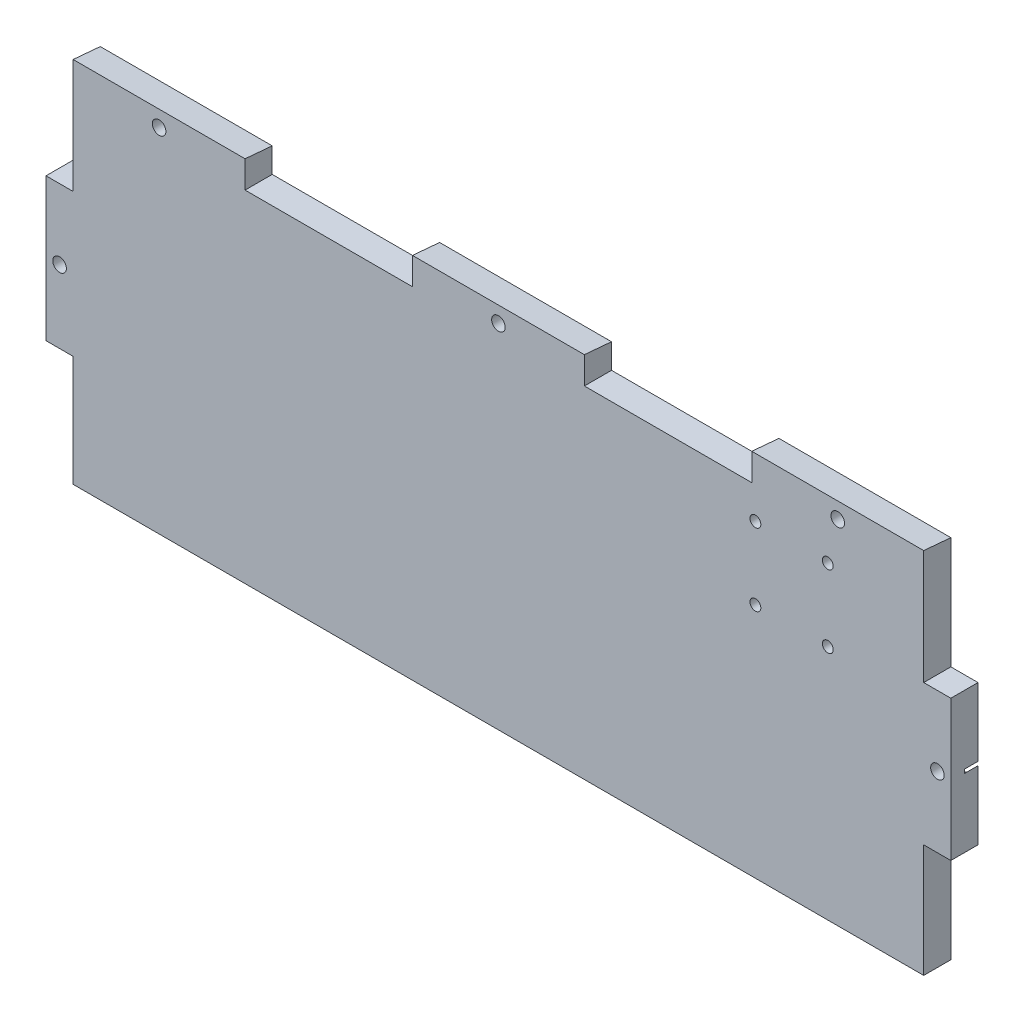
SolidWorks part; units mm, degrees
ref_plane "Plan de face" through (0, 0, 0) normal (0, 0, 1) x (1, 0, 0)
ref_plane "Plan de dessus" through (0, 0, 0) normal (0, 1, 0) x (1, 0, 0)
ref_plane "Plan de droite" through (0, 0, 0) normal (1, 0, 0) x (0, 0, -1)
sketch "Esquisse1" plane through (0, 0, 0) normal (0, 0, 1) x (1, 0, 0)
  line L1 (0, 0) -> (-188, 0)
  line L2 (0, 0) -> (0, 81.33)
  line L3 (0, 81.33) -> (-188, 81.33)
  line L4 (-188, 0) -> (-188, 81.33)
  dimension "D1" = 188
  dimension "D2" = 81.33
extrude "Boss.-Extru.1" add sketch "Esquisse1" along normal blind 6
sketch "Esquisse2" plane through (-188, 0, 0) normal (-1, 0, 0) x (0, 0, 1)
  line L0 (6, 81.33) -> (0, 80.8051)
  line L1 (0, 81.33) -> (0, 0) construction
  line L2 (6, 81.33) -> (6, 0) construction
  dimension "D1" = 85
extrude "Enlèv. mat.-Extru.2" cut sketch "Esquisse2" against normal through all and the other way through all flip side to cut contours L0
sketch "Esquisse4" plane through (-188, 0, 0) normal (-1, 0, 0) x (0, 0, 1)
  line L0 (6, 81.33) -> (6, 0) construction
  line L1 (6, 56.0675) -> (0, 56.0675)
  line L2 (6, 56.0675) -> (6, 24.5)
  line L3 (6, 24.5) -> (0, 24.5)
  line L4 (0, 56.0675) -> (0, 24.5)
  line L5 (0, 80.8051) -> (0, 0) construction
  line L6 (6, 81.33) -> (0, 80.8051) construction
  line L7 (6, 0) -> (0, 0) construction
  point P8 (3, 81.0675)
  point P11 (3, 0)
  dimension "D1" = 25
  dimension "D2" = 24.5
extrude "Boss.-Extru.2" add sketch "Esquisse4" along normal blind 6
sketch "Esquisse5" plane through (0, 0, 0) normal (1, 0, 0) x (0, 0, -1)
  line L0 (-6, 0) -> (-6, 81.33) construction
  line L1 (-6, 25) -> (0, 25)
  line L2 (-6, 25) -> (-6, 56.0675)
  line L3 (-6, 56.0675) -> (0, 56.0675)
  line L4 (0, 25) -> (0, 56.0675)
  line L5 (0, 0) -> (0, 80.8051) construction
  line L6 (-6, 0) -> (0, 0) construction
  line L7 (0, 80.8051) -> (-6, 81.33) construction
  point P10 (-3, 81.0675)
  dimension "D1" = 25
  dimension "D2" = 25
extrude "Boss.-Extru.3" add sketch "Esquisse5" along normal blind 6
sketch "Esquisse6" plane through (0, 0, 6) normal (0, 0, 1) x (1, 0, 0)
  line L0 (0, 81.33) -> (-188, 81.33) construction
  line L1 (-150, 81.33) -> (-113, 81.33)
  line L2 (-150, 81.33) -> (-150, 75.33)
  line L3 (-150, 75.33) -> (-113, 75.33)
  line L4 (-113, 81.33) -> (-113, 75.33)
  line L6 (-75, 81.33) -> (-38, 81.33)
  line L7 (-75, 81.33) -> (-75, 75.33)
  line L8 (-75, 75.33) -> (-38, 75.33)
  line L9 (-38, 81.33) -> (-38, 75.33)
  line L11 (0, 56.0675) -> (0, 81.33) construction
  dimension "D1" = 6
  dimension "D2" = 37
  dimension "D3" = 38
  dimension "D4" = 37
  dimension "D5" = 38
extrude "Enlèv. mat.-Extru.3" cut sketch "Esquisse6" against normal blind 6
sketch "Esquisse7" plane through (0, 0, 0) normal (0, 0, -1) x (-1, 0, 0)
  line L0 (113, 80.8051) -> (75, 80.8051) construction
  line L1 (113, 75.33) -> (113, 80.8051) construction
  line L2 (0, 56.0675) -> (0, 80.8051) construction
  line L3 (188, 80.8051) -> (188, 56.0675) construction
  line L4 (194, 56.0675) -> (194, 24.5) construction
  line L5 (194, 56.0675) -> (188, 56.0675) construction
  line L6 (-6, 56.0675) -> (0, 56.0675) construction
  circle A0 centre (94, 77.8051) radius 2.995
  circle A1 centre (19, 77.8051) radius 2.995
  circle A2 centre (169, 77.8051) radius 2.995
  circle A3 centre (191, 40.5675) radius 2.995
  circle A4 centre (-3.034, 40.5675) radius 2.995
  point P10 (113, 78.0675)
  point P23 (-3, 56.0675)
  dimension "D1" = 5.99
  dimension "D3" = 5.99
  dimension "D4" = 5.99
  dimension "D8" = 5.99
  dimension "D11" = 5.99
  dimension "D2" = 3
  dimension "D5" = 19
  dimension "D6" = 19
  dimension "D7" = 19
  dimension "D9" = 3
  dimension "D10" = 15.5
  dimension "D12" = 15.5
extrude "Enlèv. mat.-Extru.4" cut sketch "Esquisse7" against normal blind 3
sketch "Esquisse8" plane through (0, 0, 0) normal (0, 0, -1) x (-1, 0, 0)
  circle A0 centre (-3.034, 40.5675) radius 1.5
  circle A1 centre (19, 77.8051) radius 1.5
  circle A2 centre (94, 77.8051) radius 1.5
  circle A3 centre (169, 77.8051) radius 1.5
  circle A4 centre (191, 40.5675) radius 1.5
extrude "Enlèv. mat.-Extru.5" cut sketch "Esquisse8" against normal blind 6
sketch "Esquisse9" plane through (0, 0, 6) normal (0, 0, 1) x (1, 0, 0)
  line L0 (6, 56.0675) -> (6, 25) construction
  line L1 (0, 81.33) -> (-38, 81.33) construction
  circle A0 centre (-21.2, 68.33) radius 1.2
  circle A1 centre (-21.2, 52.33) radius 1.2
  circle A2 centre (-37.2, 68.33) radius 1.2
  circle A3 centre (-37.2, 52.33) radius 1.2
  dimension "D1" = 27.2
  dimension "D3" = 2.4
  dimension "D4" = 2.4
  dimension "D7" = 2.4
  dimension "D2" = 13
  dimension "D5" = 16
  dimension "D6" = 16
  dimension "D8" = 0
extrude "Enlèv. mat.-Extru.6" cut sketch "Esquisse9" against normal blind 10
